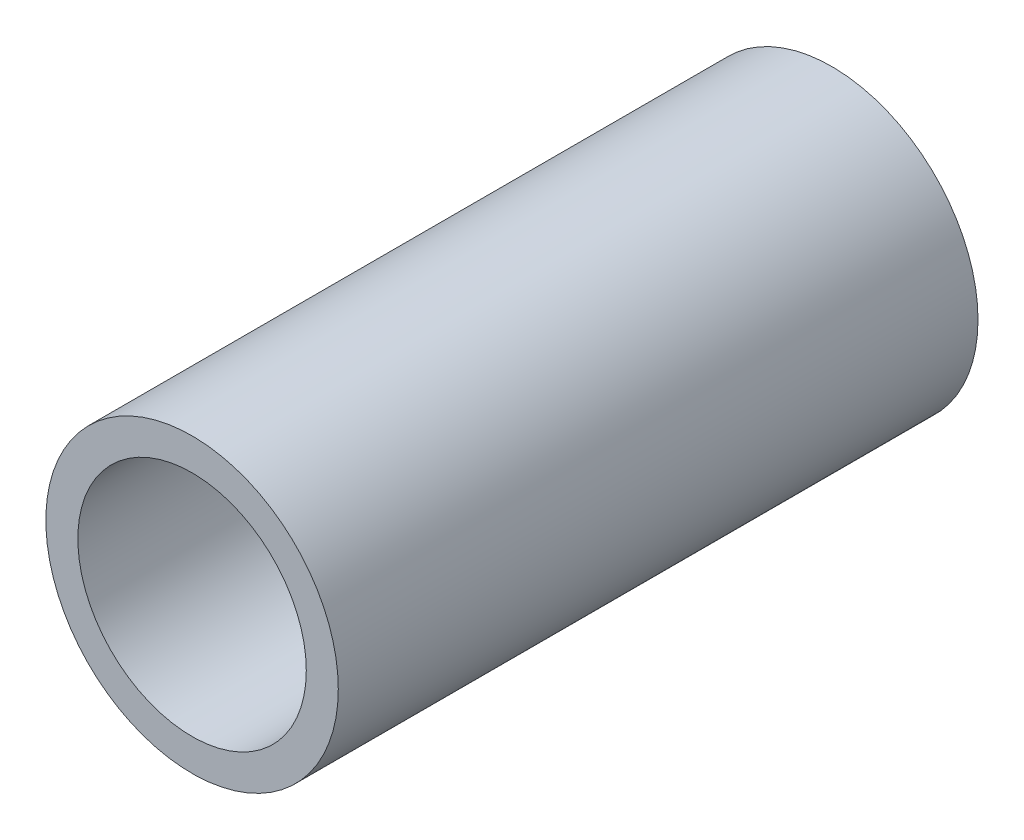
SolidWorks part; units mm, degrees
material "7075-T6 (SN)"
ref_plane "Alzado" through (0, 0, 0) normal (0, 0, 1) x (1, 0, 0)
ref_plane "Planta" through (0, 0, 0) normal (0, 1, 0) x (1, 0, 0)
ref_plane "Vista lateral" through (0, 0, 0) normal (1, 0, 0) x (0, 0, -1)
sketch "Croquis1" plane through (0, 0, 0) normal (0, 0, 1) x (1, 0, 0)
  circle A0 centre (0, 0) radius 16
  dimension "D1" = 32
extrude "Saliente-Extruir1" add sketch "Croquis1" along normal blind 70
sketch "Croquis2" plane through (0, 0, 70) normal (0, 0, 1) x (1, 0, 0)
  circle A0 centre (0, 0) radius 12.5
  dimension "D1" = 25
extrude "Cortar-Extruir1" cut sketch "Croquis2" against normal blind 69
